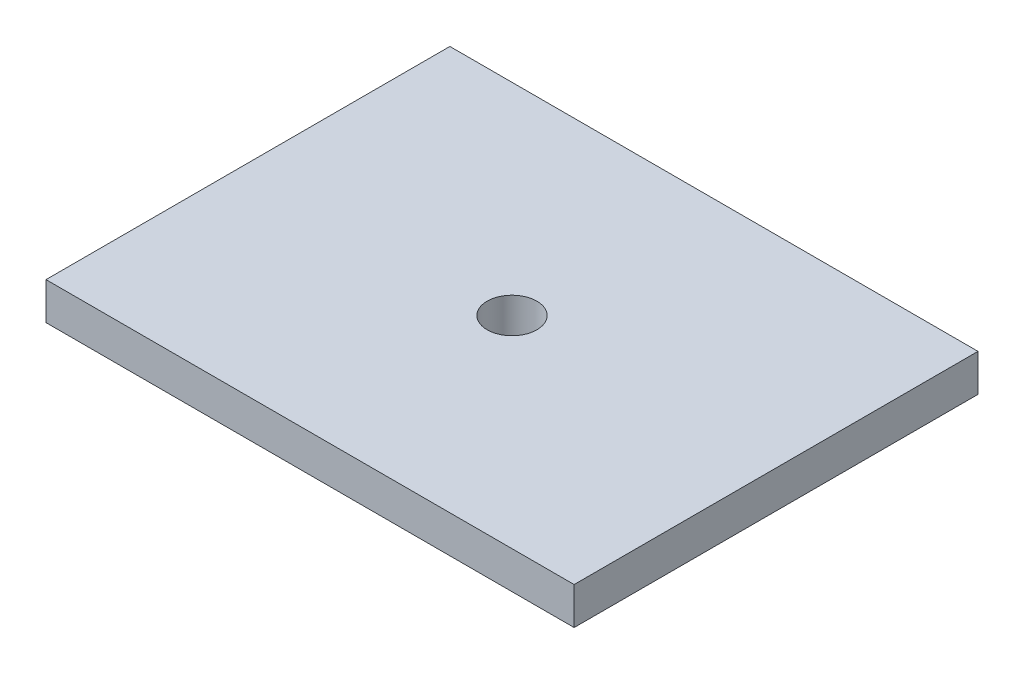
SolidWorks part; units mm, degrees
ref_plane "Спереди" through (0, 0, 0) normal (0, 0, 1) x (1, 0, 0)
ref_plane "Сверху" through (0, 0, 0) normal (0, 1, 0) x (1, 0, 0)
ref_plane "Справа" through (0, 0, 0) normal (1, 0, 0) x (0, 0, -1)
sketch "Эскиз1" plane through (0, 0, 0) normal (0, 1, 0) x (1, 0, 0)
  line L1 (-42.5, 3.665) -> (42.5, 3.665)
  line L2 (-42.5, 3.665) -> (-42.5, -61.335)
  line L3 (-42.5, -61.335) -> (42.5, -61.335)
  line L4 (42.5, 3.665) -> (42.5, -61.335)
extrude "Вытянуть1" add sketch "Эскиз1" along normal blind 6
sketch "Эскиз3" plane through (0, 6, 0) normal (0, 1, 0) x (1, 0, 0)
  line L0 (-42.5, -1.335) -> (42.5, -1.335) construction
  line L1 (-42.5, -61.335) -> (42.5, -61.335) construction
  circle A0 centre (0, -28.835) radius 4
  dimension "D1" = 32.5
extrude "Вырез-Вытянуть2" cut sketch "Эскиз3" against normal through all
